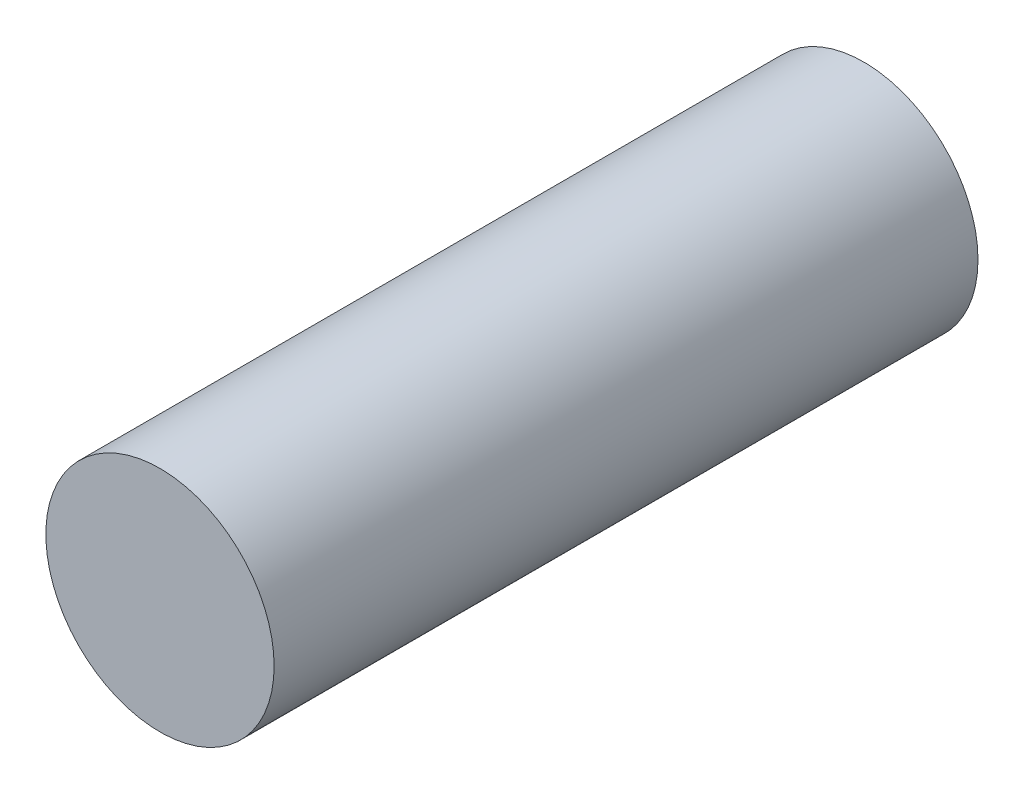
SolidWorks part; units mm, degrees
ref_plane "Front Plane" through (0, 0, 0) normal (0, 0, 1) x (1, 0, 0)
ref_plane "Top Plane" through (0, 0, 0) normal (0, 1, 0) x (1, 0, 0)
ref_plane "Right Plane" through (0, 0, 0) normal (1, 0, 0) x (0, 0, -1)
sketch "Sketch1" plane through (0, 0, 0) normal (0, 0, 1) x (1, 0, 0)
  circle A0 centre (0, 0) radius 12
extrude "Boss-Extrude1" add sketch "Sketch1" against normal blind 74
